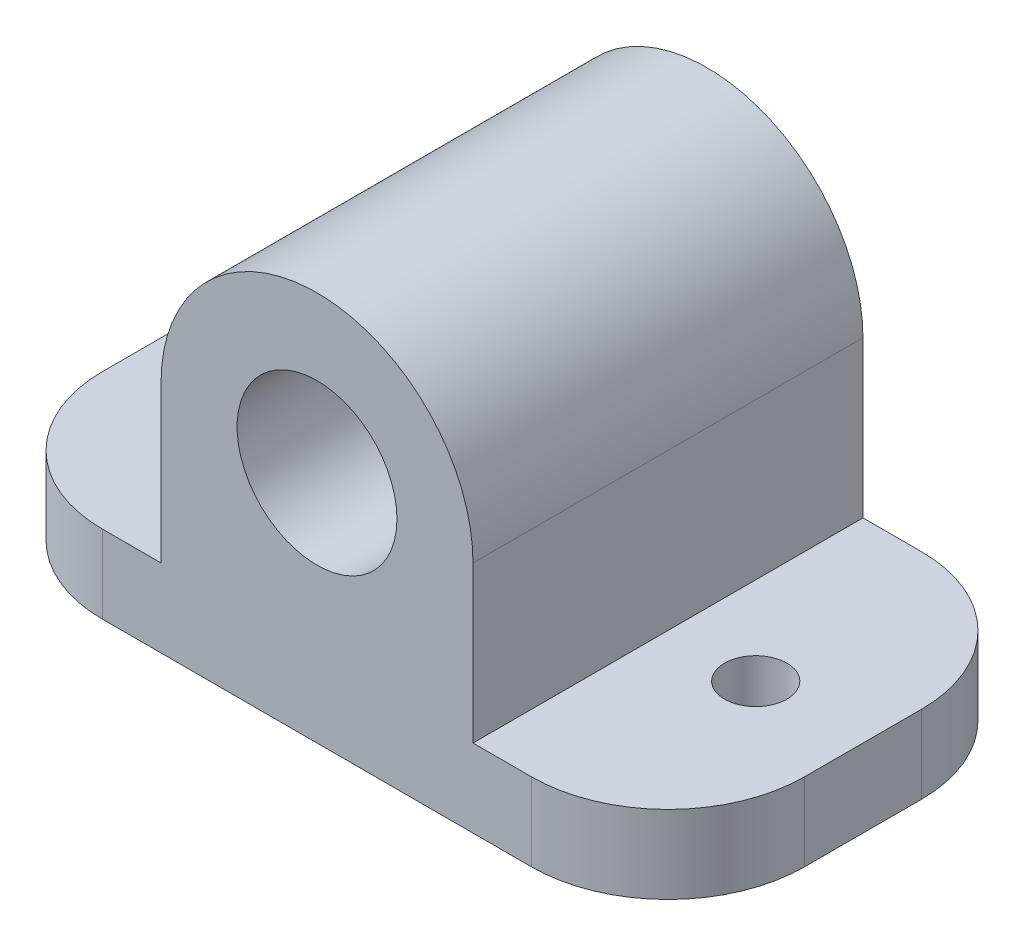
SolidWorks part; units mm, degrees
ref_plane "Plano frontal" through (0, 0, 0) normal (0, 0, 1) x (1, 0, 0)
ref_plane "Plano superior" through (0, 0, 0) normal (0, 1, 0) x (1, 0, 0)
ref_plane "Plano direito" through (0, 0, 0) normal (1, 0, 0) x (0, 0, -1)
sketch "Esboço1" plane through (0, 0, 0) normal (0, 0, 1) x (1, 0, 0)
  line L0 (-8, 0) -> (-8, -8)
  line L1 (-8, -8) -> (-18, -8)
  line L2 (-18, -8) -> (-18, -12)
  line L3 (-18, -12) -> (18, -12)
  line L4 (0, 8) -> (0, -12) construction
  line L5 (18, -8) -> (18, -12)
  line L6 (8, -8) -> (18, -8)
  line L7 (8, 0) -> (8, -8)
  circle A0 centre (0, 0) radius 4.1
  arc A1 (8, 0) -> (-8, 0) centre (0, 0) ccw
  point P3 (0, 0)
  dimension "D1" = 8.2
  dimension "D2" = 8
  dimension "D3" = 10
  dimension "D4" = 4
extrude "Ressalto-extrusão1" add sketch "Esboço1" along normal blind 20
sketch "Esboço2" plane through (0, -8, 0) normal (0, 1, 0) x (1, 0, 0)
  line L0 (0, 0) -> (0, -20) construction
  line L1 (-8, -20) -> (8, -20) construction
  line L2 (-18, -20) -> (-18, 0) construction
  circle A0 centre (-12.5, -10) radius 1.6
  circle A1 centre (12.5, -10) radius 1.6
  point P9 (0, 0)
  point P12 (-18, -10)
  dimension "D2" = 3.2
  dimension "D1" = 25
extrude "Corte-extrusão1" cut sketch "Esboço2" against normal blind 20
fillet "Filete1" radius 7 4 edges at (-18, -10, 0) (-18, -10, 20) (18, -10, 20) (18, -10, 0)
